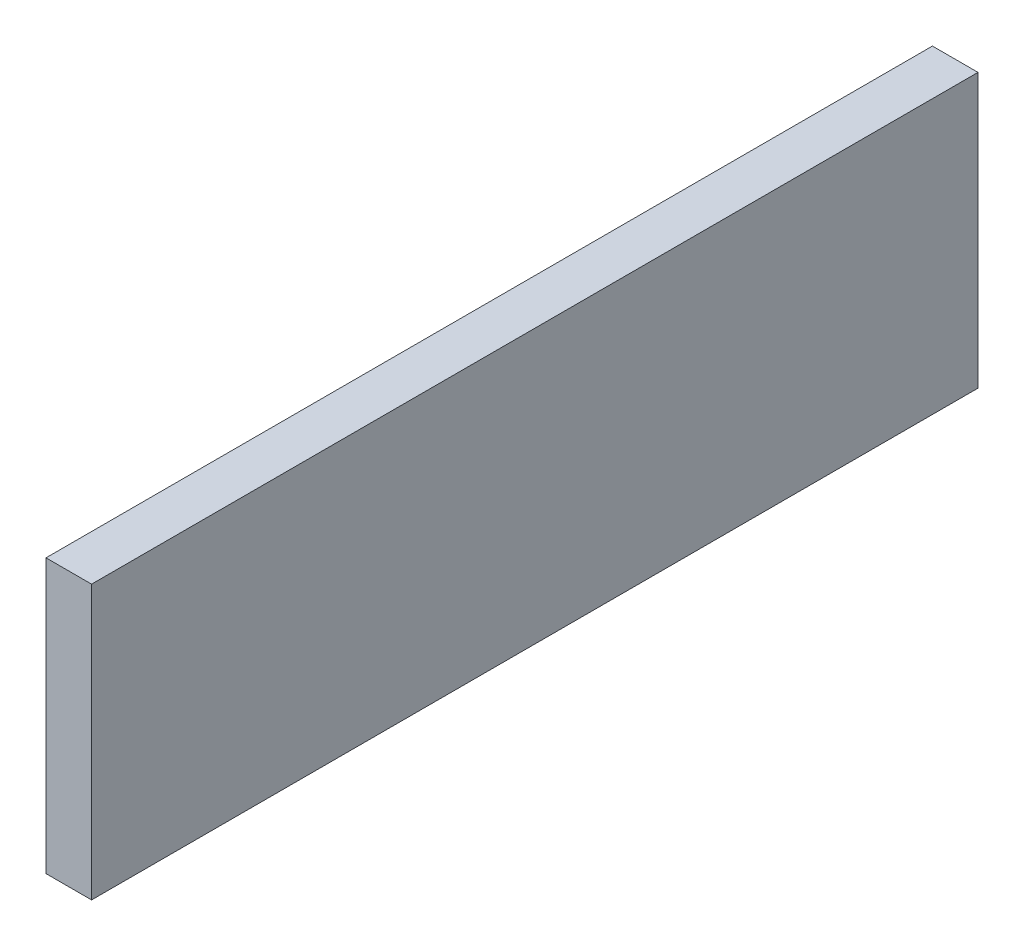
SolidWorks part; units mm, degrees
ref_plane "Ön Düzlem" through (0, 0, 0) normal (0, 0, 1) x (1, 0, 0)
ref_plane "Üst Düzlem" through (0, 0, 0) normal (0, 1, 0) x (1, 0, 0)
ref_plane "Sağ Düzlem" through (0, 0, 0) normal (1, 0, 0) x (0, 0, -1)
sketch "Çizim1" plane through (0, 0, 0) normal (1, 0, 0) x (0, 0, -1)
  line L0 (0, 0) -> (275, 0)
  line L1 (275, 0) -> (275, 84.85)
  line L2 (0, 0) -> (0, 84.85)
  line L3 (0, 84.85) -> (275, 84.85)
  dimension "D1" = 275
  dimension "D2" = 84.85
extrude "Yükseklik-Ekstrüzyon1" add sketch "Çizim1" along normal blind 14.14
